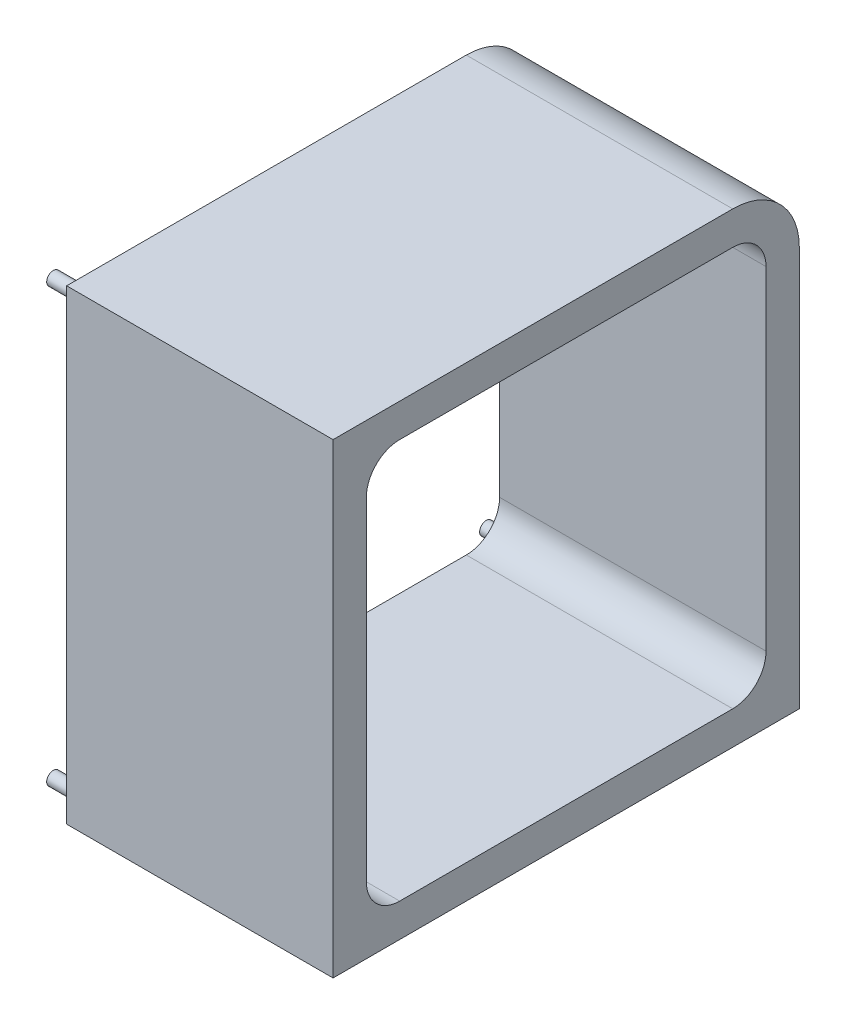
SolidWorks part; units mm, degrees
ref_plane "前视基准面" through (0, 0, 0) normal (0, 0, 1) x (1, 0, 0)
ref_plane "上视基准面" through (0, 0, 0) normal (0, 1, 0) x (1, 0, 0)
ref_plane "右视基准面" through (0, 0, 0) normal (1, 0, 0) x (0, 0, -1)
other "Configuration Table"
sketch "草图1" plane through (0, 0, 0) normal (1, 0, 0) x (0, 0, -1)
  line L1 (0, 0) -> (140, 0)
  line L2 (0, 0) -> (0, 140)
  line L3 (0, 140) -> (120, 140)
  line L4 (140, 0) -> (140, 120)
  line L5 (20, 130) -> (120, 130)
  line L6 (10, 120) -> (10, 20)
  line L7 (20, 10) -> (120, 10)
  line L8 (130, 120) -> (130, 20)
  arc A0 (120, 10) -> (130, 20) centre (120, 20) ccw
  arc A1 (20, 10) -> (10, 20) centre (20, 20) cw
  arc A2 (130, 120) -> (120, 130) centre (120, 120) ccw
  arc A3 (10, 120) -> (20, 130) centre (20, 120) cw
  arc A4 (120, 140) -> (140, 120) centre (120, 120) cw
  point P11 (130, 10)
  point P14 (10, 10)
  point P17 (130, 130)
  point P22 (140, 140)
  dimension "D7" = 10
  dimension "D8" = 20
  dimension "D1" = 140
  dimension "D2" = 140
  dimension "D3" = 120
  dimension "D4" = 120
  dimension "D5" = 10
  dimension "D6" = 10
extrude "凸台-拉伸1" add sketch "草图1" along normal blind 80
sketch "草图2" plane through (0, 0, 0) normal (-1, 0, 0) x (0, 0, 1)
  line L0 (0, 0) -> (-140, 0) construction
  line L1 (-140, 0) -> (-140, 120) construction
  line L2 (0, 140) -> (0, 0) construction
  line L3 (-120, 140) -> (0, 140) construction
  circle A1 centre (-5, 135) radius 2
  circle A2 centre (-135, 5) radius 2
  circle A3 centre (-5, 5) radius 2
  dimension "D1" = 4
  dimension "D2" = 4
  dimension "D3" = 4
  dimension "D4" = 5
  dimension "D5" = 5
  dimension "D6" = 5
  dimension "D7" = 5
  dimension "D8" = 5
  dimension "D9" = 5
extrude "凸台-拉伸2" add sketch "草图2" along normal blind 9
